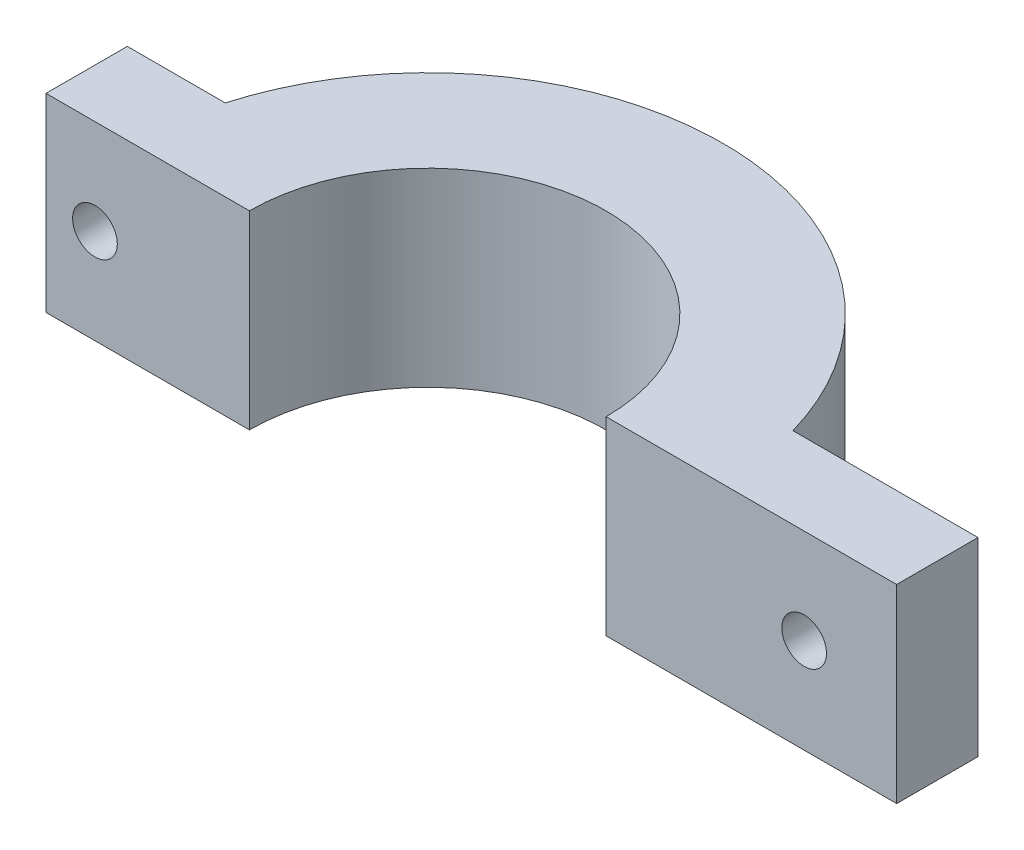
SolidWorks part; units mm, degrees
ref_plane "前基準面" through (0, 0, 0) normal (0, 0, 1) x (1, 0, 0)
ref_plane "上基準面" through (0, 0, 0) normal (0, 1, 0) x (1, 0, 0)
ref_plane "右基準面" through (0, 0, 0) normal (1, 0, 0) x (0, 0, -1)
sketch "草圖1" plane through (0, 0, 0) normal (0, 1, 0) x (1, 0, 0)
  line L1 (-15.75, 7.075) -> (15.75, 7.075)
  line L2 (-15.75, 7.075) -> (-15.75, -7.075)
  line L3 (-15.75, -7.075) -> (15.75, -7.075)
  line L4 (15.75, 7.075) -> (15.75, -7.075)
  line L5 (-15.75, 7.075) -> (15.75, -7.075) construction
  line L6 (-15.75, -7.075) -> (15.75, 7.075) construction
  point P0 (0, 0)
  dimension "D1" = 14.15
  dimension "D2" = 31.5
extrude "伸長-薄件1" add sketch "草圖1" along normal blind 12.25 thin thin type one direction wall 10
sketch "草圖2" plane through (0, 12.25, 0) normal (0, 1, 0) x (1, 0, 0)
  line L0 (-1014.255, 0) -> (48985.745, 0) construction
  line L1 (-15.75, 7.075) -> (-15.75, -7.075) construction
  line L2 (-20.75, -988.4004) -> (-20.75, 49011.5996) construction
  line L3 (-25.75, 17.075) -> (-20.75, 17.075) construction
  line L4 (-25.75, 17.075) -> (-25.75, 11.5996) construction
  line L5 (-25.75, 11.5996) -> (-20.75, 11.5996) construction
  line L6 (-20.75, 17.075) -> (-20.75, 11.5996) construction
  line L7 (25.75, 17.075) -> (20.75, 17.075) construction
  line L8 (25.75, 17.075) -> (25.75, 12.4477) construction
  line L9 (25.75, 12.4477) -> (20.75, 12.4477) construction
  line L10 (20.75, 17.075) -> (20.75, 12.4477) construction
  line L11 (20.75, -987.5523) -> (20.75, 49012.4477) construction
  circle A0 centre (-20.75, 0) radius 1.91
  circle A1 centre (20.75, 0) radius 1.91
  point P5 (-15.75, 0)
  dimension "D3" = 3.82
  dimension "D4" = 3.82
  dimension "D1" = 5
  dimension "D2" = 5
extrude "除料-伸長1" cut sketch "草圖2" against normal through all
sketch "草圖4" plane through (0, 0, 0) normal (0, -1, 0) x (1, 0, 0)
  line L0 (-1000, 0) -> (49000, 0) construction
  line L1 (25.75, 17.075) -> (25.75, -17.075) construction
  line L2 (12.75, 6.955) -> (25.75, 6.955)
  line L3 (12.75, 6.955) -> (12.75, -6.955)
  line L4 (12.75, -6.955) -> (25.75, -6.955)
  line L5 (25.75, 6.955) -> (25.75, -6.955)
  line L6 (12.75, 6.955) -> (25.75, -6.955) construction
  line L7 (12.75, -6.955) -> (25.75, 6.955) construction
  point P1 (19.25, 0)
  dimension "D1" = 13.91
  dimension "D2" = 13
extrude "填料-伸長1" add sketch "草圖4" along normal blind 74.82
sketch "草圖5" plane through (12.75, 0, 0) normal (-1, 0, 0) x (0, 0, 1)
  line L0 (6.955, -74.82) -> (6.955, 0) construction
  line L1 (-6.955, -74.82) -> (6.955, -74.82)
  line L2 (-6.955, -74.82) -> (-6.955, -58.59)
  line L3 (-6.955, -58.59) -> (6.955, -58.59)
  line L4 (6.955, -74.82) -> (6.955, -58.59)
  dimension "D1" = 16.23
extrude "填料-伸長2" add sketch "草圖5" along normal blind 16
sketch "草圖7" plane through (3.6267, -74.82, 0) normal (0, -1, 0) x (1, 0, 0)
  circle A0 centre (-30.9782, 0) radius 15.25
  dimension "D1" = 30.5
extrude "伸長-薄件2" add sketch "草圖7" against normal blind 16.23 thin
ref_plane "平面1" through (-60, 0, 0) normal (1, 0, 0) x (0, 0, -1)
ref_plane "平面2" through (-55, 0, 0) normal (1, 0, 0) x (0, 0, -1)
ref_plane "平面3" through (-60, 0, 0) normal (1, 0, 0) x (0, 0, -1)
sketch "草圖15" plane through (0, 0, -6.955) normal (0, 0, -1) x (-1, 0, 0)
  line L0 (-996.9218, -66.705) -> (49003.0782, -66.705) construction
  line L1 (3.0782, -74.82) -> (3.0782, -58.59) construction
  line L2 (-4.8359, -1058.59) -> (-4.8359, 48941.41) construction
  line L3 (3.0782, -58.59) -> (-12.75, -58.59) construction
  circle A0 centre (-4.8359, -66.705) radius 1.91
  point P5 (3.0782, -66.705)
  point P10 (-4.8359, -58.59)
  dimension "D1" = 3.82
extrude "除料-伸長6" cut sketch "草圖15" against normal through all
ref_plane "平面4" through (-60, 0, 0) normal (1, 0, 0) x (0, 0, -1)
sketch "草圖16" plane through (-60, 0, 0) normal (1, 0, 0) x (0, 0, -1)
  line L1 (6.955, -58.59) -> (-6.955, -58.59)
  line L2 (6.955, -58.59) -> (6.955, -74.82)
  line L3 (6.955, -74.82) -> (-6.955, -74.82)
  line L4 (-6.955, -58.59) -> (-6.955, -74.82)
extrude "填料-伸長4" add sketch "草圖16" along normal blind 10
sketch "草圖17" plane through (0, 0, -6.955) normal (0, 0, -1) x (-1, 0, 0)
  line L0 (-948.3753, -66.705) -> (49051.6247, -66.705) construction
  line L1 (51.6247, -74.82) -> (51.6247, -58.59) construction
  line L2 (55.8124, -1058.59) -> (55.8124, 48941.41) construction
  line L3 (51.6247, -58.59) -> (60, -58.59) construction
  circle A0 centre (55.8124, -66.705) radius 1.91
  point P5 (51.6247, -66.705)
  point P10 (55.8124, -58.59)
  dimension "D1" = 3.82
extrude "除料-伸長7" cut sketch "草圖17" against normal through all
sketch "草圖19" plane through (0, -58.59, 0) normal (0, 1, 0) x (1, 0, 0)
  line L0 (-60, 6.955) -> (-60, -6.955) construction
  line L1 (-60, 0) -> (36.5445, 0)
  line L2 (-60, 0) -> (-60, -28.4267)
  line L3 (-60, -28.4267) -> (36.5445, -28.4267)
  line L4 (36.5445, 0) -> (36.5445, -28.4267)
extrude "除料-伸長8" cut sketch "草圖19" against normal blind 41 and the other way blind 83
sketch "草圖21" plane through (25.75, 0, 0) normal (1, 0, 0) x (0, 0, -1)
  line L0 (0, -74.82) -> (0, 12.25) construction
  line L1 (0, -36.2363) -> (18.5662, -36.2363)
  line L2 (0, -36.2363) -> (0, 14.4577)
  line L3 (0, 14.4577) -> (18.5662, 14.4577)
  line L4 (18.5662, -36.2363) -> (18.5662, 14.4577)
extrude "除料-伸長10" cut sketch "草圖21" against normal blind 57
sketch "草圖22" plane through (0, -36.2363, 0) normal (0, 1, 0) x (1, 0, 0)
  line L1 (12.75, 0) -> (25.75, 0)
  line L2 (12.75, 0) -> (12.75, 6.955)
  line L3 (12.75, 6.955) -> (25.75, 6.955)
  line L4 (25.75, 0) -> (25.75, 6.955)
extrude "除料-伸長11" cut sketch "草圖22" against normal blind 57
